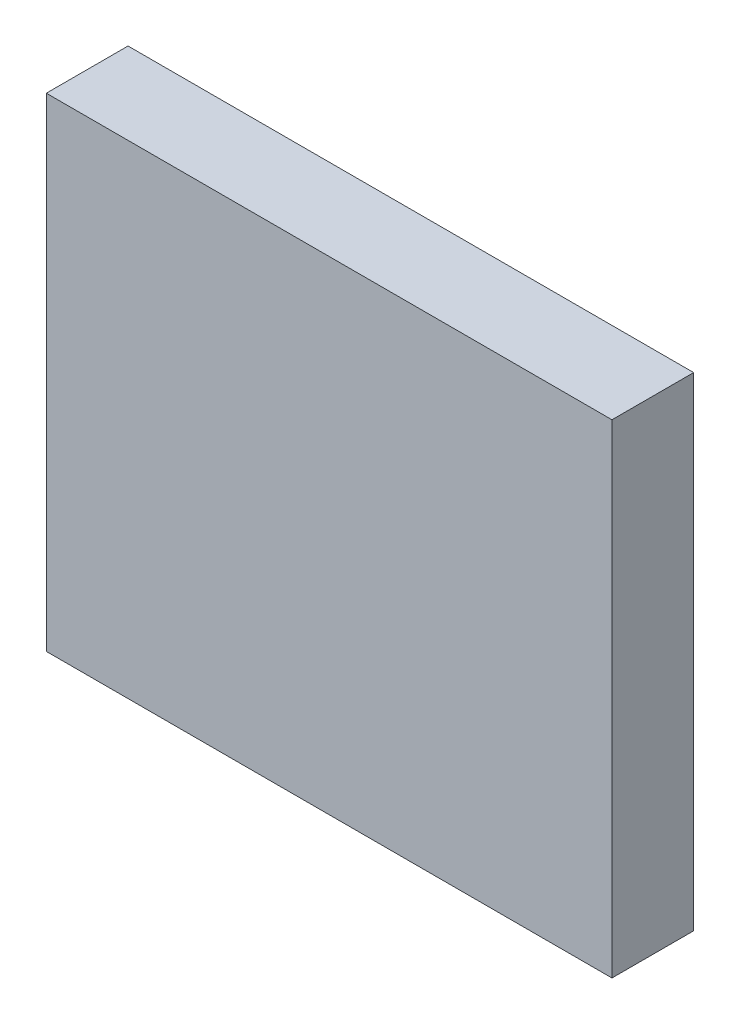
SolidWorks part; units mm, degrees
ref_plane "Front Plane" through (0, 0, 0) normal (0, 0, 1) x (1, 0, 0)
ref_plane "Top Plane" through (0, 0, 0) normal (0, 1, 0) x (1, 0, 0)
ref_plane "Right Plane" through (0, 0, 0) normal (1, 0, 0) x (0, 0, -1)
sketch "Sketch1" plane through (0, 0, 0) normal (0, 0, 1) x (1, 0, 0)
  line L0 (-3.6195, 3.2233) -> (3.302, 3.2233)
  line L1 (3.302, 3.2233) -> (3.302, -2.6924)
  line L2 (3.302, -2.6924) -> (-3.6195, -2.6924)
  line L3 (-3.6195, -2.6924) -> (-3.6195, 3.2233)
extrude "Component_Outline" add sketch "Sketch1" along normal blind 1 separate body
sketch3d "3DSketch1"
  line L0 (0, 0, 0) -> (1, 0, 0)
  line L1 (0, 0, 0) -> (0, 1, 0)
  line L2 (0, 0, 0) -> (0, 0, 1)
  point P0 (0, 0, 0)
